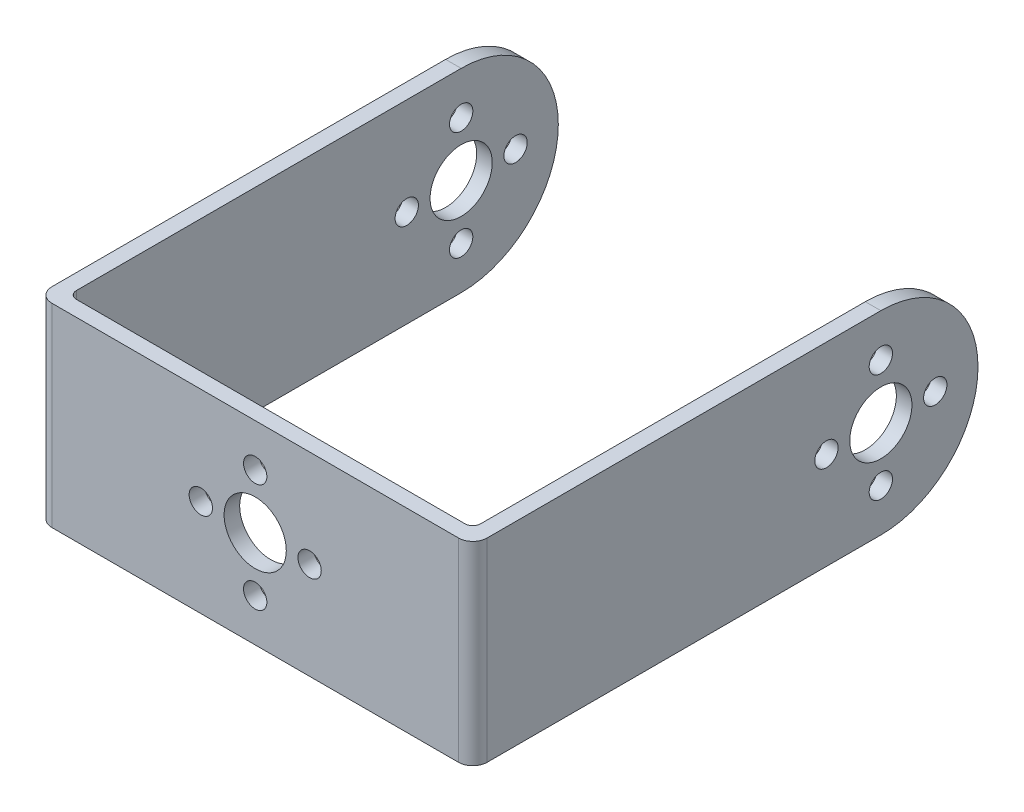
SolidWorks part; units mm, degrees
ref_plane "Alzado" through (0, 0, 0) normal (0, 0, 1) x (1, 0, 0)
ref_plane "Planta" through (0, 0, 0) normal (0, 1, 0) x (1, 0, 0)
ref_plane "Vista lateral" through (0, 0, 0) normal (1, 0, 0) x (0, 0, -1)
sketch "Croquis1" plane through (0, 0, 0) normal (0, 1, 0) x (1, 0, 0)
  line L0 (0, 1.84) -> (0, 65)
  line L1 (0, 65) -> (2, 65)
  line L2 (2, 65) -> (2, 3)
  line L3 (3, 2) -> (53, 2)
  line L4 (54, 3) -> (54, 65)
  line L5 (54, 65) -> (56, 65)
  line L6 (56, 65) -> (56, 1.84)
  line L7 (54.16, 0) -> (1.84, 0)
  arc A0 (53, 2) -> (54, 3) centre (53, 3) ccw
  arc A1 (2, 3) -> (3, 2) centre (3, 3) ccw
  arc A2 (56, 1.84) -> (54.16, 0) centre (54.16, 1.84) cw
  arc A3 (0, 1.84) -> (1.84, 0) centre (1.84, 1.84) ccw
  point P15 (56, 0)
  point P18 (0, 0)
  dimension "D7" = 1
  dimension "D8" = 1.84
  dimension "D1" = 2
  dimension "D2" = 2
  dimension "D3" = 56
  dimension "D4" = 65
  dimension "D5" = 65
  dimension "D6" = 2
extrude "Saliente-Extruir2" add sketch "Croquis1" along normal blind 25 contours L2 A1 L3 A0 L4 L5 L6 A2 L7 A3 L0 L1
sketch "Croquis2" plane through (0, 0, 0) normal (0, 0, 1) x (1, 0, 0)
  line L0 (28, 0) -> (28, 25) construction
  line L1 (54.16, 0) -> (1.84, 0) construction
  line L2 (54.16, 25) -> (1.84, 25) construction
  circle A0 centre (28, 12.5) radius 4
  circle A1 centre (28, 19.5) radius 1.5
  circle A2 centre (28, 5.5) radius 1.5
  circle A3 centre (35, 12.5) radius 1.5
  circle A4 centre (21, 12.5) radius 1.5
  dimension "D1" = 7
  dimension "D2" = 14
  dimension "D3" = 7
  dimension "D4" = 14
extrude "Cortar-Extruir1" cut sketch "Croquis2" against normal blind 10
sketch "Croquis3" plane through (56, 0, 0) normal (1, 0, 0) x (0, 0, -1)
  line L0 (65, 25) -> (1.84, 25) construction
  line L1 (65, 25) -> (65, 0) construction
  line L2 (65, 0) -> (1.84, 0) construction
  line L3 (52.5, 25) -> (65, 25)
  line L4 (65, 25) -> (65, 0)
  line L5 (65, 0) -> (52.5, 0)
  circle A0 centre (52.5, 12.5) radius 12.5
  circle A1 centre (52.5, 12.5) radius 4
  circle A2 centre (52.5, 19.5) radius 1.5
  circle A3 centre (59.5, 12.5) radius 1.5
  circle A4 centre (52.5, 5.5) radius 1.5
  circle A5 centre (45.5, 12.5) radius 1.5
  line M2 (1.84, 0) -> (65, 0)
  line M3 (65, 0) -> (65, 25)
  line M4 (65, 25) -> (1.84, 25)
  dimension "D1" = 7
  dimension "D2" = 7
  dimension "D3" = 7
  dimension "D4" = 14
extrude "Cortar-Extruir2" cut sketch "Croquis3" against normal blind 60 contours A0 L4 M4 | A0 M2 M3 | A1 | A5 | A2 | A3 | A4
